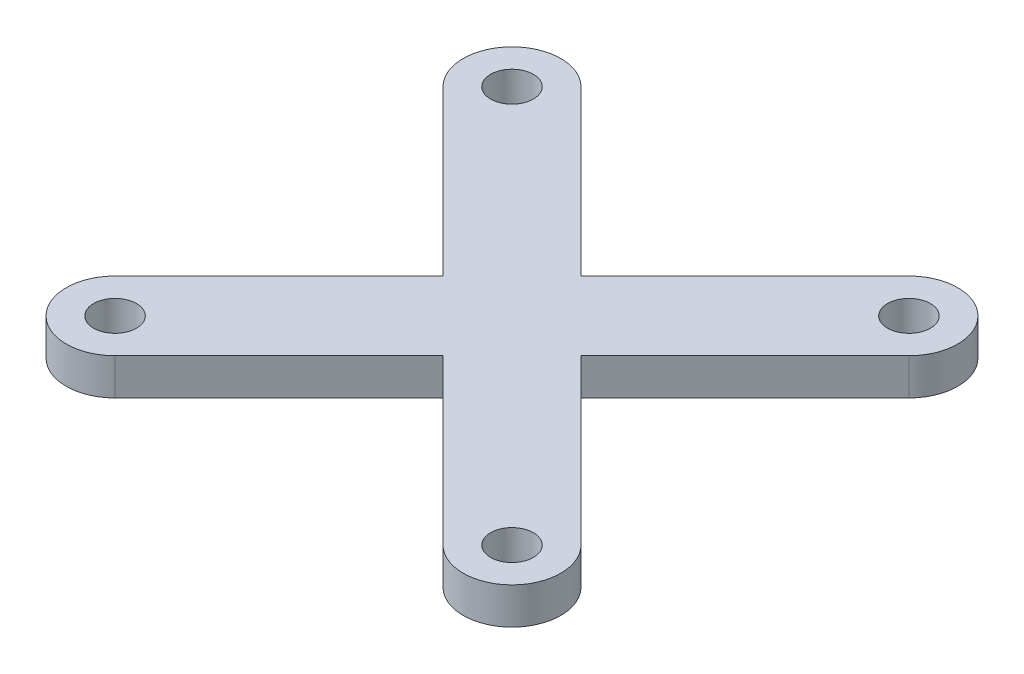
SolidWorks part; units mm, degrees
ref_plane "前视基准面" through (0, 0, 0) normal (0, 0, 1) x (1, 0, 0)
ref_plane "上视基准面" through (0, 0, 0) normal (0, 1, 0) x (1, 0, 0)
ref_plane "右视基准面" through (0, 0, 0) normal (1, 0, 0) x (0, 0, -1)
sketch "Sketch1" plane through (0, 0, 0) normal (0, 1, 0) x (1, 0, 0)
  circle A0 centre (0, 0) radius 11.9
  circle A1 centre (0, 0) radius 9.9
  dimension "D1" = 23.8
  dimension "D2" = 19.8
extrude "Boss-Extrude3" add sketch "Sketch1" along normal blind 15 contours A1 | A0
sketch "Sketch4" plane through (0, 0, 0) normal (0, -1, 0) x (1, 0, 0)
  circle A0 centre (0, 0) radius 9.9
extrude "Boss-Extrude4" add sketch "Sketch4" against normal blind 5.1
sketch "Sketch7" plane through (0, 0, 0) normal (1, 0, 0) x (0, 0, -1)
  line L0 (0, 15) -> (0, -4.8)
  arc A0 (0, -4.8) -> (0, 15) centre (0, 5.1) ccw
  dimension "D2" = 9.9
  dimension "D1" = 5.1
revolve "Cut-Revolve2" cut sketch "Sketch7" angle 360 about L0
sketch "Sketch12" plane through (0, 15, 0) normal (0, 1, 0) x (1, 0, 0)
  circle A0 centre (0, 0) radius 19
  circle A1 centre (0, 0) radius 11.9
  dimension "D1" = 38
extrude "Boss-Extrude8" add sketch "Sketch12" against normal blind 3
sketch "Sketch14" plane through (0, 15, 0) normal (0, 1, 0) x (1, 0, 0)
  line L0 (0, 0) -> (0, 22.9912) construction
  line L1 (0, 0) -> (27.8368, 0) construction
  line L2 (0, 0) -> (-27.3663, 0) construction
  line L3 (0, 0) -> (0, -24.0336) construction
  circle A0 centre (0, 15.15) radius 1.755
  circle A1 centre (-15.15, 0) radius 1.755
  circle A2 centre (0, -15.15) radius 1.755
  circle A3 centre (15.15, 0) radius 1.755
  dimension "D1" = 3.51
  dimension "D2" = 3.51
  dimension "D3" = 3.51
  dimension "D4" = 3.51
  dimension "D5" = 15.15
  dimension "D6" = 15.15
  dimension "D7" = 15.15
  dimension "D8" = 15.15
extrude "Cut-Extrude4" cut sketch "Sketch14" against normal blind 3
sketch "Sketch15" plane through (0, 0, 0) normal (1, 0, 0) x (0, 0, -1)
  line L1 (-19, 12) -> (19, 12)
  line L2 (-19, 12) -> (-19, -4.08)
  line L3 (-19, -4.08) -> (19, -4.08)
  line L4 (19, 12) -> (19, -4.08)
extrude "Cut-Extrude5" cut sketch "Sketch15" against normal blind 20 and the other way blind 25
sketch "Sketch16" plane through (0, 15, 0) normal (0, 1, 0) x (1, 0, 0)
  circle A0 centre (0, 0) radius 9.9
extrude "Boss-Extrude9" add sketch "Sketch16" against normal blind 3
sketch "Sketch17" plane through (0, 15, 0) normal (0, 1, 0) x (1, 0, 0)
  line L0 (-20, 20) -> (20, -20) construction
  line L1 (-20, 20) -> (20, 20)
  line L2 (-20, 20) -> (-20, -20)
  line L3 (-20, -20) -> (20, -20)
  line L4 (20, 20) -> (20, -20)
  line L5 (20, 20) -> (-20, -20) construction
  circle A0 centre (0, 0) radius 19
  dimension "D1" = 20
  dimension "D2" = 40
  dimension "D3" = 20
  dimension "D4" = 40
extrude "Boss-Extrude10" add sketch "Sketch17" against normal blind 3
sketch "Sketch20" plane through (0, 15, 0) normal (0, 1, 0) x (1, 0, 0)
  line L1 (-30, 30) -> (30, 30)
  line L2 (-30, 30) -> (-30, -30)
  line L3 (-30, -30) -> (30, -30)
  line L4 (30, 30) -> (30, -30)
  line L5 (-20, 20) -> (20, 20)
  line L6 (-20, 20) -> (-20, -20)
  line L7 (-20, -20) -> (20, -20)
  line L8 (20, 20) -> (20, -20)
  dimension "D1" = 30
  dimension "D2" = 30
  dimension "D3" = 30
  dimension "D4" = 30
extrude "Boss-Extrude11" add sketch "Sketch20" against normal blind 3
sketch "Sketch21" plane through (0, 15, 0) normal (0, 1, 0) x (1, 0, 0)
  line L0 (0, 0) -> (25.3354, 25.3354) construction
  line L1 (0, 0) -> (-24.4377, -24.4377) construction
  line L2 (0, 0) -> (26.151, -26.151) construction
  line L3 (0, 0) -> (-23.3223, 23.3223) construction
  line L4 (-20.2635, 16.2635) -> (-20.2635, -17.8436)
  line L5 (-16.2635, 20.2635) -> (16.2635, 20.2635)
  line L6 (20.2635, 16.2635) -> (20.2635, -16.2635)
  line L7 (-16.2635, -20.2635) -> (16.2635, -20.2635)
  circle A0 centre (0, 0) radius 27
  circle A1 centre (0, 0) radius 19
  circle A2 centre (-16.2635, 16.2635) radius 4
  circle A3 centre (16.2635, -16.2635) radius 4
  circle A4 centre (-16.2635, -16.2635) radius 4
  circle A5 centre (16.2635, 16.2635) radius 4
  circle A6 centre (-16.2635, 16.2635) radius 1.755
  circle A7 centre (16.2635, 16.2635) radius 1.755
  circle A8 centre (16.2635, -16.2635) radius 1.755
  circle A9 centre (-16.2635, -16.2635) radius 1.755
  dimension "D5" = 23
  dimension "D6" = 8
  dimension "D1" = 54
  dimension "D2" = 38
  dimension "D4" = 8
  dimension "D8" = 8
  dimension "D10" = 8
  dimension "D11" = 3.51
  dimension "D12" = 3.51
  dimension "D13" = 3.51
  dimension "D14" = 3.51
  dimension "D3" = 23
  dimension "D7" = 23
  dimension "D9" = 23
extrude "Cut-Extrude7" cut sketch "Sketch21" against normal blind 3 contours A6 | A9 | A7 | A8
sketch "Sketch23" plane through (0, 15, 0) normal (0, 1, 0) x (1, 0, 0)
  line L0 (-16.2635, 16.2635) -> (-21.8925, 16.2635) construction
  line L1 (-16.2635, 16.2635) -> (-16.2635, 21.8596) construction
  line L2 (16.2635, 16.2635) -> (21.4673, 16.2635) construction
  line L3 (16.2635, 16.2635) -> (16.2635, 20.813) construction
  line L4 (16.2635, -16.2635) -> (22.3518, -16.2635) construction
  line L5 (16.2635, -16.2635) -> (16.2635, -21.2937) construction
  line L6 (-16.2635, -16.2635) -> (-21.8925, -16.2635) construction
  line L7 (-16.2635, -16.2635) -> (-16.2635, -23.6212) construction
  line L8 (-20.2635, -16.2635) -> (-20.2635, 16.2635)
  line L9 (-16.2635, 20.2635) -> (16.2635, 20.2635)
  line L10 (20.2635, 16.2635) -> (20.2635, -16.2635)
  line L11 (16.2635, -20.2635) -> (-16.2635, -20.2635)
  line L13 (-30, 30) -> (30, 30)
  line L14 (-30, 30) -> (-30, -30)
  line L15 (-30, -30) -> (30, -30)
  line L16 (30, 30) -> (30, -30)
  arc A0 (-20.2635, 16.2635) -> (-16.2635, 20.2635) centre (-16.2635, 16.2635) cw
  arc A1 (20.2635, 16.2635) -> (16.2635, 20.2635) centre (16.2635, 16.2635) ccw
  arc A2 (20.2635, -16.2635) -> (16.2635, -20.2635) centre (16.2635, -16.2635) cw
  arc A3 (-20.2635, -16.2635) -> (-16.2635, -20.2635) centre (-16.2635, -16.2635) ccw
  dimension "D1" = 4
  dimension "D2" = 4
  dimension "D3" = 4
  dimension "D4" = 4
extrude "Cut-Extrude9" cut sketch "Sketch23" against normal blind 3
sketch "Sketch24" plane through (0, 15, 0) normal (0, 1, 0) x (1, 0, 0)
  line L0 (-16.2635, 16.2635) -> (-10.9345, 21.5924) construction
  line L1 (-16.2635, 16.2635) -> (-22.8443, 9.6826) construction
  line L2 (-16.2635, -16.2635) -> (-10.081, -22.4459) construction
  line L3 (-16.2635, -16.2635) -> (-24.3971, -8.1299) construction
  line L4 (16.2635, -16.2635) -> (24.3971, -8.1299) construction
  line L5 (16.2635, -16.2635) -> (7.8699, -24.657) construction
  line L6 (16.2635, 16.2635) -> (22.4871, 10.0398) construction
  line L7 (16.2635, 16.2635) -> (10.2251, 22.3019) construction
  line L8 (-13.435, -19.0919) -> (19.0919, 13.435) construction
  line L9 (-19.0919, -13.435) -> (13.435, 19.0919) construction
  line L10 (-19.0919, 13.435) -> (13.435, -19.0919) construction
  line L11 (-13.435, 19.0919) -> (19.0919, -13.435) construction
  line L12 (-19.0919, 13.435) -> (-5.6569, 0)
  line L13 (-5.6569, 0) -> (-19.0919, -13.435)
  line L14 (-13.435, 19.0919) -> (0, 5.6569)
  line L15 (0, 5.6569) -> (13.435, 19.0919)
  line L16 (19.0919, 13.435) -> (5.6569, 0)
  line L17 (5.6569, 0) -> (19.0919, -13.435)
  line L18 (-13.435, -19.0919) -> (0, -5.6569)
  line L19 (0, -5.6569) -> (13.435, -19.0919)
  arc A0 (-13.435, 19.0919) -> (-19.0919, 13.435) centre (-16.2635, 16.2635) ccw
  arc A1 (-19.0919, -13.435) -> (-13.435, -19.0919) centre (-16.2635, -16.2635) ccw
  arc A2 (19.0919, -13.435) -> (13.435, -19.0919) centre (16.2635, -16.2635) cw
  arc A3 (13.435, 19.0919) -> (19.0919, 13.435) centre (16.2635, 16.2635) cw
  circle A4 centre (-16.2635, 16.2635) radius 1.755
  circle A5 centre (16.2635, 16.2635) radius 1.755
  circle A6 centre (16.2635, -16.2635) radius 1.755
  circle A7 centre (-16.2635, -16.2635) radius 1.755
extrude "Boss-Extrude12" add sketch "Sketch24" along normal blind 3
sketch "Sketch25" plane through (0, 0, 20.2635) normal (0, 0, 1) x (1, 0, 0)
  line L1 (-23.2567, 15) -> (31.2888, 15)
  line L2 (-23.2567, 15) -> (-23.2567, 8.4874)
  line L3 (-23.2567, 8.4874) -> (31.2888, 8.4874)
  line L4 (31.2888, 15) -> (31.2888, 8.4874)
extrude "Cut-Extrude10" cut sketch "Sketch25" against normal blind 42 and the other way blind 16
